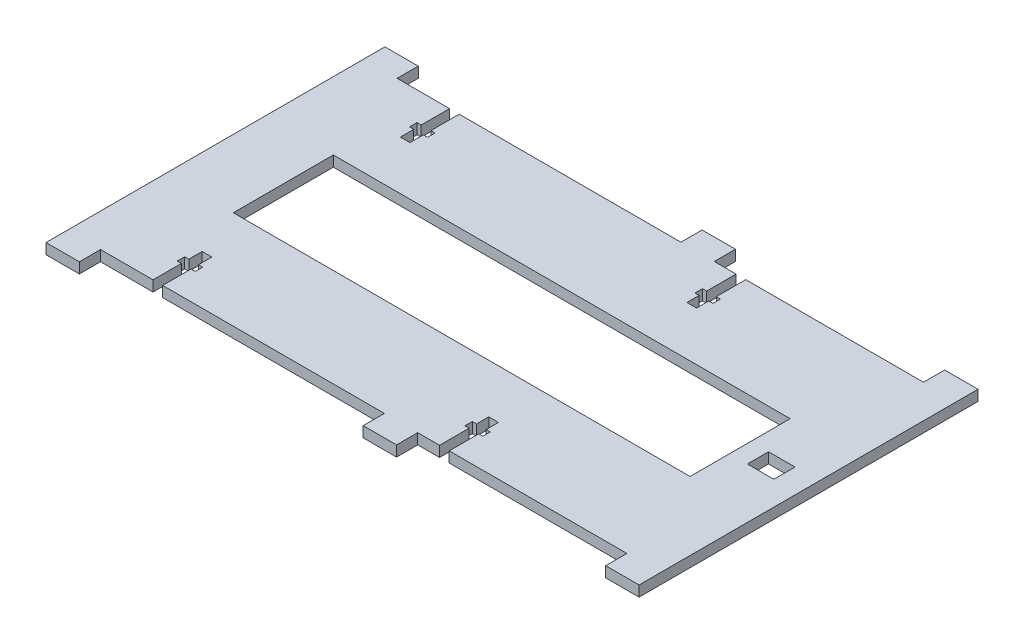
SolidWorks part; units mm, degrees
ref_plane "Front Plane" through (0, 0, 0) normal (0, 0, 1) x (1, 0, 0)
ref_plane "Top Plane" through (0, 0, 0) normal (0, 1, 0) x (1, 0, 0)
ref_plane "Right Plane" through (0, 0, 0) normal (1, 0, 0) x (0, 0, -1)
sketch "Sketch1" plane through (0, 0, 0) normal (0, 1, 0) x (1, 0, 0)
  line L0 (-67.1586, 70.4843) -> (-67.1586, 74.4928)
  line L1 (-92.8881, 91.5843) -> (-82.8881, 91.5843)
  line L2 (-92.8881, 91.5843) -> (-92.8881, -10.0157)
  line L3 (84.9141, 91.5843) -> (84.9141, -10.0157)
  line L5 (-64.2586, 85.2343) -> (2.2019, 85.2343)
  line L6 (-67.1586, 85.2343) -> (-67.1586, 76.7428)
  line L7 (-67.1586, 70.4843) -> (-64.2586, 70.4843)
  line L8 (-64.2586, 85.2343) -> (-64.2586, 76.7428)
  line L9 (-68.4086, 76.7428) -> (-67.1586, 76.7428)
  line L10 (-68.4086, 76.7428) -> (-68.4086, 74.4928)
  line L11 (-68.4086, 74.4928) -> (-67.1586, 74.4928)
  line L12 (-63.0086, 76.7428) -> (-63.0086, 74.4928)
  line L13 (18.7441, 70.4843) -> (18.7441, 74.1476)
  line L14 (-82.8881, 91.5843) -> (-82.8881, 85.2343)
  line L15 (-82.8881, 85.2343) -> (-67.1586, 85.2343)
  line L16 (2.2019, 91.5843) -> (2.2019, 85.2343)
  line L17 (-64.2586, 70.4843) -> (-64.2586, 74.4928)
  line L18 (-64.2586, 74.4928) -> (-63.0086, 74.4928)
  line L19 (-64.2586, 76.7428) -> (-63.0086, 76.7428)
  line L20 (2.2019, 91.5843) -> (12.2019, 91.5843)
  line L21 (21.6441, 85.2343) -> (74.9141, 85.2343)
  line L22 (18.7441, 85.2343) -> (18.7441, 76.3976)
  line L23 (18.7441, 70.4843) -> (21.6441, 70.4843)
  line L24 (21.6441, 85.2343) -> (21.6441, 76.3976)
  line L25 (17.4941, 76.3976) -> (18.7441, 76.3976)
  line L26 (17.4941, 76.3976) -> (17.4941, 74.1476)
  line L27 (17.4941, 74.1476) -> (18.7441, 74.1476)
  line L28 (22.8941, 76.3976) -> (22.8941, 74.1476)
  line L29 (12.2019, 91.5843) -> (12.2019, 85.2343)
  line L30 (12.2019, 85.2343) -> (18.7441, 85.2343)
  line L31 (74.9141, 91.5843) -> (74.9141, 85.2343)
  line L32 (21.6441, 70.4843) -> (21.6441, 74.1476)
  line L33 (21.6441, 74.1476) -> (22.8941, 74.1476)
  line L34 (21.6441, 76.3976) -> (22.8941, 76.3976)
  line L35 (74.9141, 91.5843) -> (84.9141, 91.5843)
  line L36 (-82.8881, -3.6657) -> (-67.1586, -3.6657)
  line L37 (74.9141, -10.0157) -> (84.9141, -10.0157)
  line L38 (21.6441, 5.171) -> (22.8941, 5.171)
  line L39 (21.6441, 7.421) -> (22.8941, 7.421)
  line L40 (21.6441, 11.0843) -> (21.6441, 7.421)
  line L41 (74.9141, -10.0157) -> (74.9141, -3.6657)
  line L42 (12.2019, -3.6657) -> (18.7441, -3.6657)
  line L43 (12.2019, -10.0157) -> (12.2019, -3.6657)
  line L44 (22.8941, 5.171) -> (22.8941, 7.421)
  line L45 (17.4941, 7.421) -> (18.7441, 7.421)
  line L46 (17.4941, 5.171) -> (17.4941, 7.421)
  line L47 (17.4941, 5.171) -> (18.7441, 5.171)
  line L48 (21.6441, -3.6657) -> (21.6441, 5.171)
  line L49 (18.7441, 11.0843) -> (21.6441, 11.0843)
  line L50 (18.7441, -3.6657) -> (18.7441, 5.171)
  line L51 (21.6441, -3.6657) -> (74.9141, -3.6657)
  line L52 (2.2019, -10.0157) -> (12.2019, -10.0157)
  line L53 (-64.2586, 4.8258) -> (-63.0086, 4.8258)
  line L54 (-64.2586, 7.0758) -> (-63.0086, 7.0758)
  line L55 (-64.2586, 11.0843) -> (-64.2586, 7.0758)
  line L56 (2.2019, -10.0157) -> (2.2019, -3.6657)
  line L57 (-82.8881, -10.0157) -> (-82.8881, -3.6657)
  line L58 (18.7441, 11.0843) -> (18.7441, 7.421)
  line L59 (-63.0086, 4.8258) -> (-63.0086, 7.0758)
  line L60 (-68.4086, 7.0758) -> (-67.1586, 7.0758)
  line L61 (-68.4086, 4.8258) -> (-68.4086, 7.0758)
  line L62 (-68.4086, 4.8258) -> (-67.1586, 4.8258)
  line L63 (-64.2586, -3.6657) -> (-64.2586, 4.8258)
  line L64 (-67.1586, 11.0843) -> (-64.2586, 11.0843)
  line L65 (-67.1586, -3.6657) -> (-67.1586, 4.8258)
  line L66 (-64.2586, -3.6657) -> (2.2019, -3.6657)
  line L67 (-92.8881, -10.0157) -> (-82.8881, -10.0157)
  line L68 (-67.1586, 11.0843) -> (-67.1586, 7.0758)
  line L69 (-72.5449, 55.7843) -> (64.3996, 55.7843)
  line L70 (-72.5449, 55.7843) -> (-72.5449, 25.7843)
  line L71 (-72.5449, 25.7843) -> (64.3996, 25.7843)
  line L72 (64.3996, 55.7843) -> (64.3996, 25.7843)
  line L75 (69.7412, 43.9593) -> (77.6787, 43.9593)
  line L76 (69.7412, 43.9593) -> (69.7412, 37.6093)
  line L77 (69.7412, 37.6093) -> (77.6787, 37.6093)
  line L78 (77.6787, 43.9593) -> (77.6787, 37.6093)
  point P76 (-72.5449, 40.7843)
  point P79 (69.7412, 40.7843)
  dimension "D1" = 1.25
  dimension "D2" = 2.9
  dimension "D3" = 1.25
  dimension "D4" = 2.25
  dimension "D5" = 14.75
  dimension "D6" = 1.25
  dimension "D7" = 1.25
  dimension "D8" = 2.25
  dimension "D9" = 14.75
  dimension "D10" = 10
  dimension "D11" = 10
  dimension "D12" = 10
  dimension "D13" = 6.35
  dimension "D14" = 6.35
  dimension "D15" = 53.27
  dimension "D16" = 101.6
  dimension "D17" = 95.09
  dimension "D18" = 30
  dimension "D19" = 101.6
  dimension "D20" = 50.8
  dimension "D21" = 7.9375
  dimension "D22" = 6.35
  dimension "D23" = 50.8
  dimension "D24" = 6.35
extrude "Extrude1" add sketch "Sketch1" along normal blind 3.175
